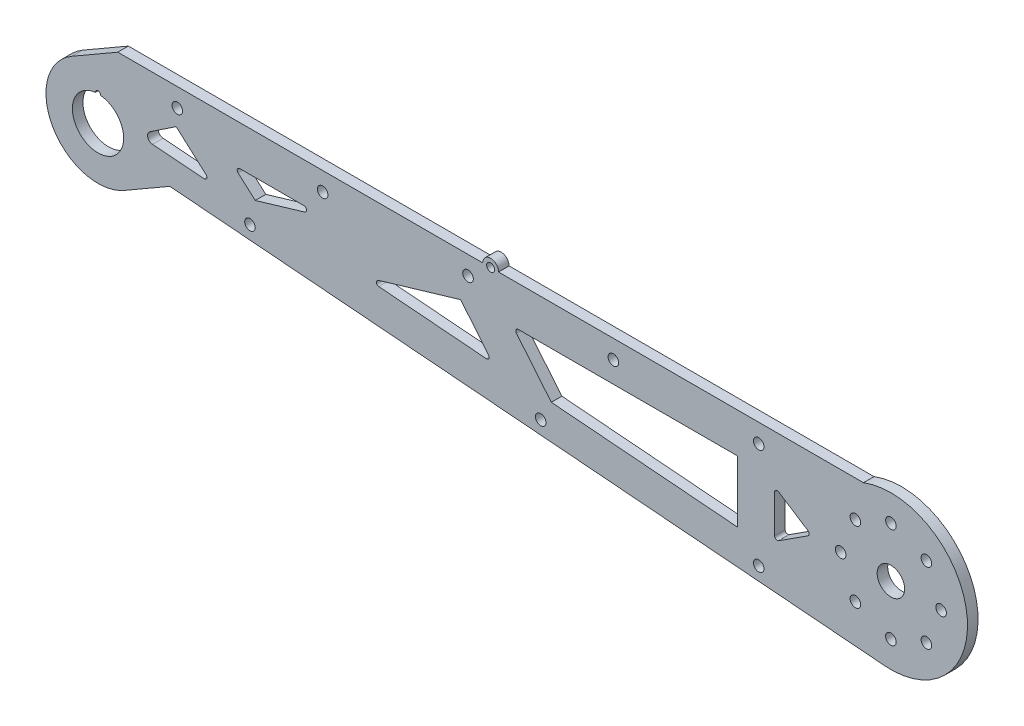
SolidWorks part; units mm, degrees
ref_plane "前视基准面" through (0, 0, 0) normal (0, 0, 1) x (1, 0, 0)
ref_plane "上视基准面" through (0, 0, 0) normal (0, 1, 0) x (1, 0, 0)
ref_plane "右视基准面" through (0, 0, 0) normal (1, 0, 0) x (0, 0, -1)
sketch "草图1" plane through (0, 0, 0) normal (0, 0, 1) x (1, 0, 0)
  line L0 (0, 0) -> (300, 0) construction
  line L1 (0, 0) -> (-15.3092, 26.5163) construction
  line L6 (-9.85, 17.0607) -> (7.4705, 27.0607)
  line L7 (9.85, -17.0607) -> (27.1705, -7.0607)
  line L8 (300, 0) -> (350.6731, 87.7683) construction
  line L9 (27.1705, -7.0607) -> (297.6656, -28.9059)
  line L10 (250, -20) -> (24.502, -1.7888) construction
  line L11 (289.6247, 27.0607) -> (7.4705, 27.0607)
  line L12 (250, 0) -> (250, 20) construction
  line L13 (167.5, -13.3373) -> (195, 20) construction
  line L14 (167.5, -13.3373) -> (140, 20) construction
  line L15 (85, 20) -> (57.5, -4.4537) construction
  line L16 (57.5, -4.4537) -> (30, 20) construction
  circle A0 centre (0, 0) radius 9.7
  circle A1 centre (300, 0) radius 19 construction
  circle A2 centre (300, 0) radius 5.2
  circle A3 centre (319, 0) radius 2
  circle A18 centre (313.435, -13.435) radius 2
  circle A19 centre (300, -19) radius 2
  circle A20 centre (286.565, -13.435) radius 2
  circle A21 centre (281, 0) radius 2
  circle A22 centre (286.565, 13.435) radius 2
  circle A23 centre (300, 19) radius 2
  circle A24 centre (313.435, 13.435) radius 2
  circle A25 centre (0, 0) radius 19.7 construction
  arc A26 (9.85, -17.0607) -> (-9.85, 17.0607) centre (0, 0) cw
  circle A27 centre (300, 0) radius 29 construction
  arc A28 (289.6247, 27.0607) -> (297.6656, -28.9059) centre (299.9992, -0.0097) cw
  circle A29 centre (250, 20) radius 2
  circle A30 centre (195, 20) radius 2
  circle A31 centre (140, 20) radius 2
  circle A32 centre (85, 20) radius 2
  circle A33 centre (30, 20) radius 2
  circle A35 centre (250, -20) radius 2
  circle A37 centre (167.5, -13.3373) radius 2
  circle A38 centre (57.5, -4.4537) radius 2
  dimension "D1" = 19.4
  dimension "D3" = 38
  dimension "D4" = 10.4
  dimension "D5" = 4
  dimension "D6" = 8
  dimension "D7" = 10
  dimension "D10" = 10
  dimension "D13" = 4
  dimension "D2" = 300
  dimension "D8" = 120
  dimension "D9" = 20
  dimension "D11" = 120
  dimension "D12" = 50
  dimension "D14" = 5
extrude "凸台-拉伸1" add sketch "草图1" along normal blind 4
sketch "草图2" plane through (0, 0, 0) normal (0, 0, -1) x (-1, 0, 0)
  line L3 (-137.1976, 10.8253) -> (-106.0437, 1.591)
  line L4 (-106.2474, -0.3645) -> (-146.9399, -3.6508)
  line L5 (-147.7919, -2.0177) -> (-137.1976, 10.8253)
  line L9 (-242, 12) -> (-159.0911, 12)
  line L10 (-77.9672, 12) -> (-53.6651, 12)
  line L11 (-53.0006, 10.2527) -> (-59.4917, 4.4807)
  line L12 (-171.5176, -5.6357) -> (-158.3196, 10.3637)
  line L13 (-242, -11.3279) -> (-171.5176, -5.6357)
  line L14 (-242, 12) -> (-242, -11.3279)
  line L18 (-59.4917, 4.4807) -> (-78.2514, 10.0412)
  line L22 (-268.63, 0.8403) -> (-257.5421, 7.9938)
  line L23 (-256, 7.1535) -> (-256, -7.1535)
  line L24 (-257.5421, -7.9938) -> (-268.63, -0.8403)
  line L32 (-19.6317, 7.0786) -> (-29.5619, 13.6987)
  line L33 (-29.5619, 13.6987) -> (-40.8603, 3.6519)
  line L34 (-40.1186, 1.9076) -> (-20.5867, 3.4204)
  arc A2 (-20.5867, 3.4204) -> (-19.6317, 7.0786) centre (-20.7411, 5.4145) ccw
  arc A3 (-40.1186, 1.9076) -> (-40.8603, 3.6519) centre (-40.1958, 2.9046) cw
  arc A4 (-158.3196, 10.3637) -> (-159.0911, 12) centre (-159.0911, 11) ccw
  arc A5 (-53.0006, 10.2527) -> (-53.6651, 12) centre (-53.6651, 11) ccw
  arc A6 (-78.2514, 10.0412) -> (-77.9672, 12) centre (-77.9672, 11) cw
  arc A7 (-106.2474, -0.3645) -> (-106.0437, 1.591) centre (-106.3279, 0.6323) ccw
  arc A8 (-146.9399, -3.6508) -> (-147.7919, -2.0177) centre (-147.0204, -2.6541) cw
  arc A9 (-256, 7.1535) -> (-257.5421, 7.9938) centre (-257, 7.1535) ccw
  arc A10 (-256, -7.1535) -> (-257.5421, -7.9938) centre (-257, -7.1535) cw
  arc A11 (-268.63, -0.8403) -> (-268.63, 0.8403) centre (-268.0879, 0) cw
  dimension "D1" = 2
  dimension "D3" = 1
  dimension "D2" = 1
extrude "切除-拉伸1" cut sketch "草图2" against normal blind 10
sketch "草图3" plane through (0, 0, 0) normal (0, 0, -1) x (-1, 0, 0)
  line L0 (-289.6247, 27.0607) -> (-7.4705, 27.0607) construction
  circle A0 centre (-148.5476, 27.0607) radius 3
extrude "凸台-拉伸2" add sketch "草图3" against normal blind 4
sketch "草图4" plane through (0, 0, 0) normal (0, 0, -1) x (-1, 0, 0)
  circle A0 centre (-148.5476, 27.0607) radius 1.5
extrude "切除-拉伸2" cut sketch "草图4" against normal blind 4
sketch "草图5" plane through (0, 0, 0) normal (0, 0, -1) x (-1, 0, 0)
  circle A0 centre (0, 9.7) radius 1
  circle A1 centre (0, 0) radius 9.7 construction
extrude "切除-拉伸3" cut sketch "草图5" against normal blind 10
